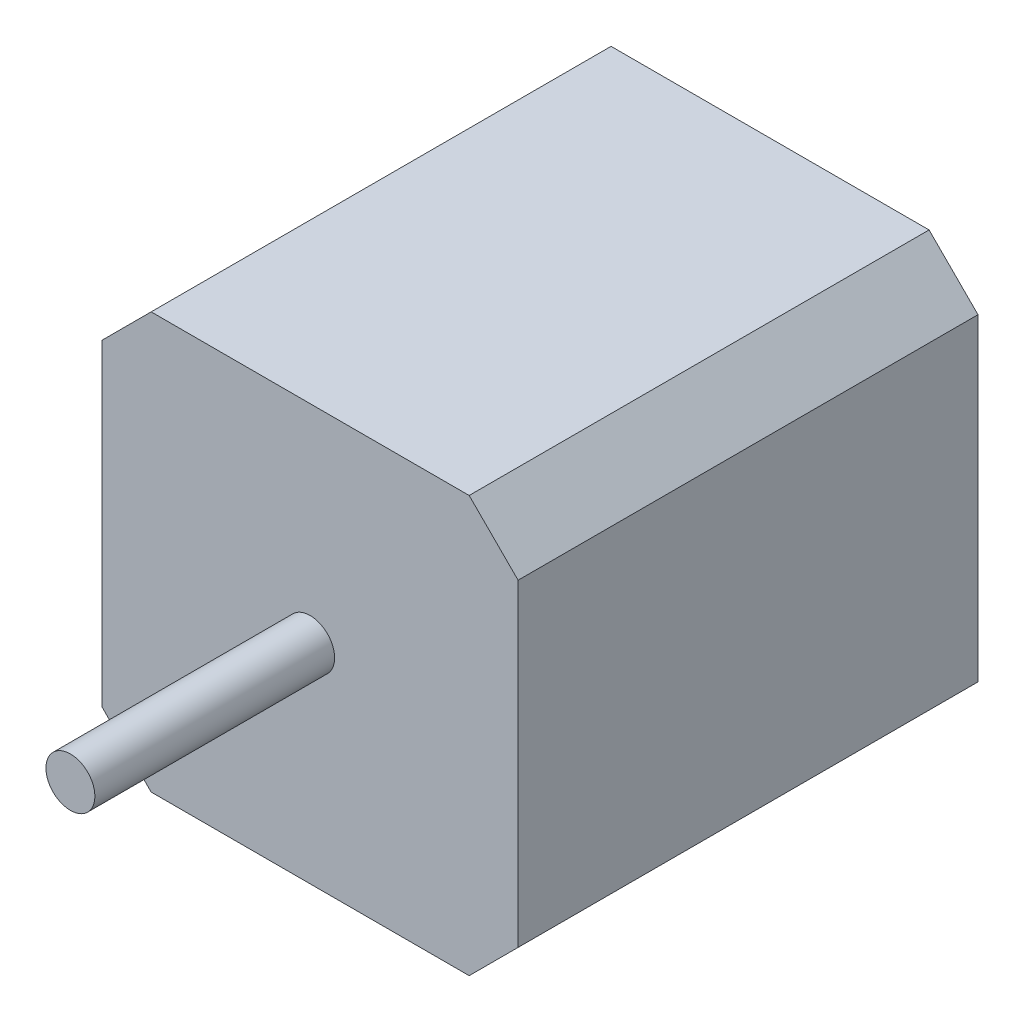
SolidWorks part; units mm, degrees
ref_plane "Front Plane" through (0, 0, 0) normal (0, 0, 1) x (1, 0, 0)
ref_plane "Top Plane" through (0, 0, 0) normal (0, 1, 0) x (1, 0, 0)
ref_plane "Right Plane" through (0, 0, 0) normal (1, 0, 0) x (0, 0, -1)
sketch "Sketch1" plane through (0, 0, 0) normal (0, 0, 1) x (1, 0, 0)
  line L1 (-41.6448, 27.598) -> (0.8552, 27.598)
  line L2 (-41.6448, 27.598) -> (-41.6448, -14.902)
  line L3 (-41.6448, -14.902) -> (0.8552, -14.902)
  line L4 (0.8552, 27.598) -> (0.8552, -14.902)
  dimension "D1" = 42.5
extrude "Boss-Extrude1" add sketch "Sketch1" along normal blind 47
chamfer "Chamfer1" distance 5 angle 45 4 edges at (0.8552, 27.598, 23.5) (0.8552, -14.902, 23.5) (-41.6448, -14.902, 23.5) (-41.6448, 27.598, 23.5)
sketch "Sketch2" plane through (0, 0, 47) normal (0, 0, 1) x (1, 0, 0)
  line L0 (-39.1448, 25.098) -> (-1.6448, -12.402) construction
  line L1 (-36.6448, 27.598) -> (-41.6448, 22.598) construction
  line L2 (-4.1448, -14.902) -> (0.8552, -9.902) construction
  circle A0 centre (-20.3948, 6.348) radius 2.5
extrude "Boss-Extrude2" add sketch "Sketch2" along normal blind 24.5
